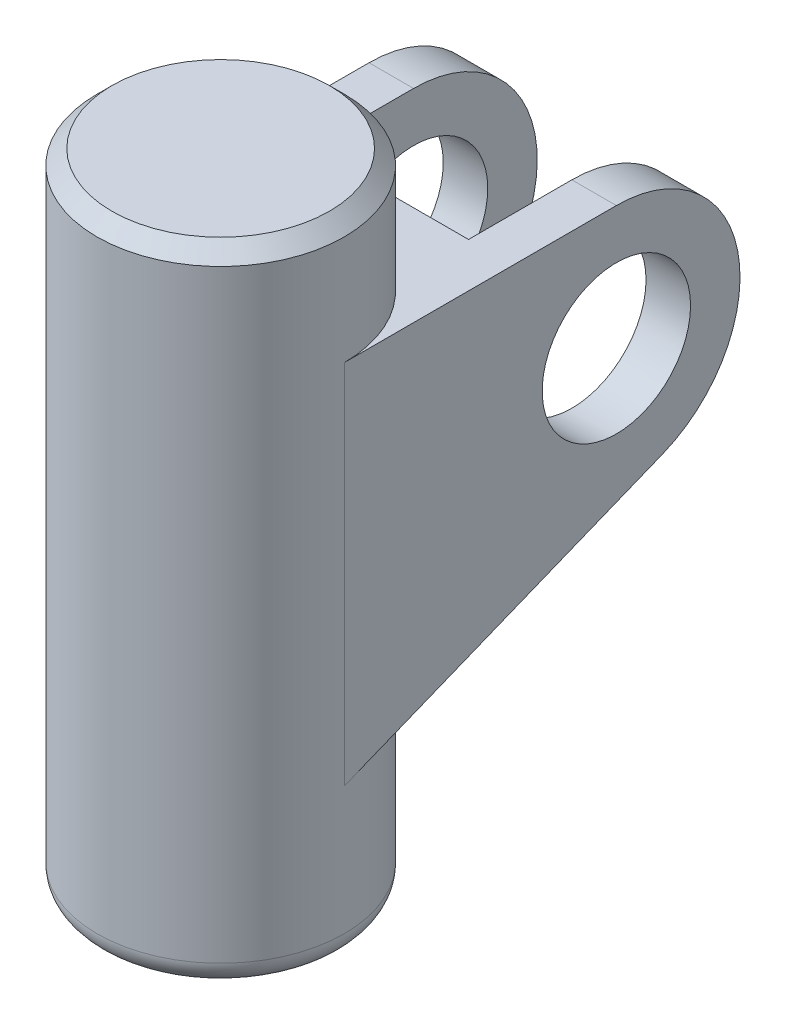
SolidWorks part; units mm, degrees
ref_plane "up基准面" through (0, 0, 0) normal (0, 0, 1) x (1, 0, 0)
ref_plane "前基准面" through (0, 0, 0) normal (0, 1, 0) x (1, 0, 0)
ref_plane "右视基准面" through (0, 0, 0) normal (1, 0, 0) x (0, 0, -1)
sketch "草图10" plane through (0, 0, 0) normal (1, 0, 0) x (0, 0, -1)
  line L0 (0, 25) -> (-55, 25)
  line L1 (9.3524, -23.1848) -> (-55, -49.1435)
  line L2 (-55, 25) -> (-55, -49.1435)
  arc A0 (0, 25) -> (9.3524, -23.1848) centre (0, 0) cw
  dimension "D1" = 25
  dimension "D2" = 55
extrude "凸台-拉伸8" add sketch "草图10" along normal mid plane 50
sketch "草图12" plane through (0, 25, 0) normal (0, 1, 0) x (1, 0, 0)
  line L0 (25, -55) -> (-25, -55) construction
  circle A0 centre (0, -55) radius 25
extrude "凸台-拉伸9" add sketch "草图12" against normal blind 80 from surface at -25 starting at plane "前基准面"
fillet "圆角1" radius 5 1 edges at (0, -80, 80)
sketch "草图13" plane through (0, -80, 0) normal (0, -1, 0) x (1, 0, 0)
  circle A0 centre (0, 55) radius 15
extrude "切除-拉伸1" cut sketch "草图13" against normal blind 80
sketch "草图14" plane through (0, 25, 0) normal (0, 1, 0) x (1, 0, 0)
  circle A0 centre (0, -55) radius 25
extrude "凸台-拉伸10" add sketch "草图14" along normal mid plane 50
chamfer "倒角1" distance 3 angle 45 1 edges at (0, 50, 80)
sketch "草图15" plane through (25, 0, 0) normal (1, 0, 0) x (0, 0, -1)
  circle A0 centre (0, 0) radius 15
extrude "切除-拉伸2" cut sketch "草图15" against normal blind 55
sketch "草图16" plane through (0, 0, 0) normal (1, 0, 0) x (0, 0, -1)
  line L1 (-20.8876, -38.8031) -> (30.4349, -38.8031)
  line L2 (-20.8876, -38.8031) -> (-20.8876, 33.533)
  line L3 (-20.8876, 33.533) -> (30.4349, 33.533)
  line L4 (30.4349, -38.8031) -> (30.4349, 33.533)
extrude "切除-拉伸3" cut sketch "草图16" against normal mid plane 32
